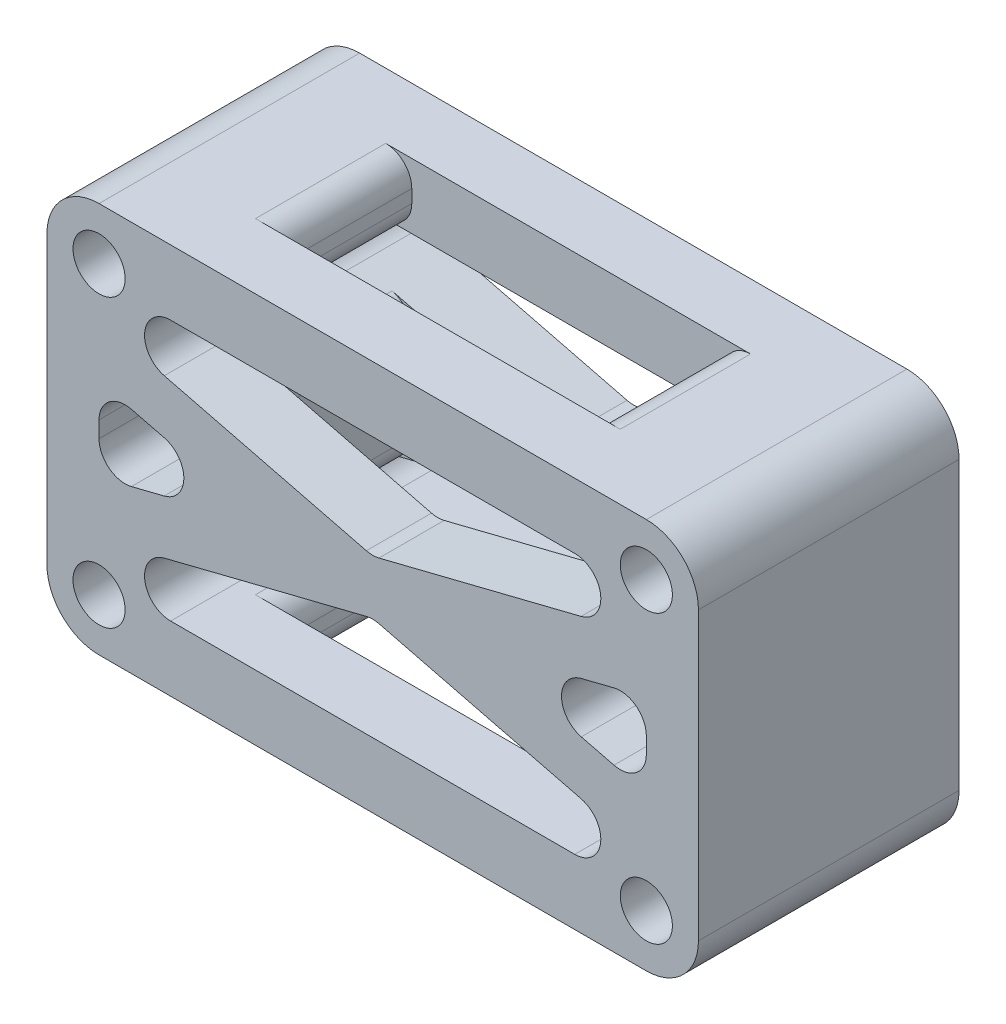
SolidWorks part; units mm, degrees
material "ABS"
ref_plane "Front" through (0, 0, 0) normal (0, 0, 1) x (1, 0, 0)
ref_plane "Top" through (0, 0, 0) normal (0, 1, 0) x (1, 0, 0)
ref_plane "Right" through (0, 0, 0) normal (1, 0, 0) x (0, 0, -1)
sketch "草图1" plane through (0, 0, 0) normal (0, 0, 1) x (1, 0, 0)
  line L1 (-12.5, -7.5) -> (12.5, -7.5)
  line L2 (-12.5, -7.5) -> (-12.5, 7.5)
  line L3 (-12.5, 7.5) -> (12.5, 7.5)
  line L4 (12.5, -7.5) -> (12.5, 7.5)
  line L5 (0, 7.5) -> (0, -7.5) construction
  line L6 (-12.5, 0) -> (12.5, 0) construction
  point P0 (0, 0)
  dimension "D1" = 15
  dimension "D2" = 25
extrude "凸台-拉伸1" add sketch "草图1" along normal blind 10
sketch "草图2" plane through (0, 0, 10) normal (0, 0, 1) x (1, 0, 0)
  line L0 (-0.2425, -1.0914) -> (-7.9963, -3.0299) construction
  line L1 (7.9963, -3.0299) -> (0.2425, -1.0914) construction
  line L2 (-0.2425, -1.0914) -> (-7.9963, -3.0299)
  line L3 (7.9963, -3.0299) -> (0.2425, -1.0914)
  line L4 (-1.5989, 0) -> (2.2438, 0) construction
  line L5 (7.7538, 5) -> (-7.7538, 5)
  line L6 (7.9963, 3.0299) -> (0.2425, 1.0914)
  line L7 (-0.2425, 1.0914) -> (-7.9963, 3.0299)
  line L8 (0, 0.633) -> (0, -0.5198) construction
  line L9 (-9.2575, -1.2836) -> (-8.0037, -0.9701)
  line L10 (-9.2575, 1.2836) -> (-8.0037, 0.9701)
  line L11 (10.5, 0.3134) -> (10.5, -0.3134)
  line L12 (7.7538, -5) -> (-7.7538, -5) construction
  line L13 (7.7538, -5) -> (-7.7538, -5)
  line L14 (12.5, -7.5) -> (12.5, 7.5) construction
  line L15 (-10.5, 0.3134) -> (-10.5, -0.3134)
  line L16 (9.2575, 1.2836) -> (8.0037, 0.9701)
  line L17 (9.2575, -1.2836) -> (8.0037, -0.9701)
  arc A0 (0.2425, -1.0914) -> (-0.2425, -1.0914) centre (0, -2.0616) ccw construction
  arc A1 (0.2425, -1.0914) -> (-0.2425, -1.0914) centre (0, -2.0616) ccw
  arc A2 (-7.9963, -3.0299) -> (-7.7538, -5) centre (-7.7538, -4) ccw construction
  arc A3 (7.7538, -5) -> (7.9963, -3.0299) centre (7.7538, -4) ccw construction
  arc A4 (-7.9963, -3.0299) -> (-7.7538, -5) centre (-7.7538, -4) ccw
  arc A5 (7.7538, -5) -> (7.9963, -3.0299) centre (7.7538, -4) ccw
  arc A6 (0.2425, 1.0914) -> (-0.2425, 1.0914) centre (0, 2.0616) cw
  arc A7 (8.0037, 0.9701) -> (8.0037, -0.9701) centre (8.2462, 0) ccw
  arc A8 (7.7538, 5) -> (7.9963, 3.0299) centre (7.7538, 4) cw
  arc A9 (-7.9963, 3.0299) -> (-7.7538, 5) centre (-7.7538, 4) cw
  arc A10 (10.5, -0.3134) -> (9.2575, -1.2836) centre (9.5, -0.3134) cw
  arc A11 (9.2575, 1.2836) -> (10.5, 0.3134) centre (9.5, 0.3134) cw
  arc A12 (-9.2575, 1.2836) -> (-10.5, 0.3134) centre (-9.5, 0.3134) ccw
  arc A13 (-10.5, -0.3134) -> (-9.2575, -1.2836) centre (-9.5, -0.3134) ccw
  arc A14 (-8.0037, 0.9701) -> (-8.0037, -0.9701) centre (-8.2462, 0) cw
  point P6 (-10.4472, 4.1056)
  point P7 (9.5528, -5.8944)
  point P8 (-9.5528, 5.8944)
  point P9 (10.4472, -4.1056)
  point P10 (-9.5528, -5.8944)
  point P11 (10.4472, 4.1056)
  point P12 (-10.4472, -4.1056)
  point P13 (9.5528, 5.8944)
  point P14 (-10.5211, -6.8779)
  point P15 (11.4789, 5.1221)
  point P16 (-11.4789, 5.1221)
  point P17 (10.5211, -6.8779)
  point P18 (-11.4789, -5.1221)
  point P19 (10.5211, 6.8779)
  point P20 (-10.5211, 6.8779)
  point P21 (11.4789, -5.1221)
  dimension "D2" = 1
  dimension "D1" = 2
fillet "圆角4" radius 2 4 edges at (-12.5, 7.5, 5) (12.5, -7.5, 5) (12.5, 7.5, 5) (-12.5, -7.5, 5)
extrude "切除-拉伸3" cut sketch "草图2" against normal blind 10
sketch "草图3" plane through (0, 0, 10) normal (0, 0, 1) x (1, 0, 0)
  line L0 (0, 3.0049) -> (0, -1.7372) construction
  line L1 (-3.0112, 0) -> (3.1966, 0) construction
  circle A0 centre (-10.5, 5.5) radius 1
  circle A1 centre (10.5, 5.5) radius 1
  circle A2 centre (10.5, -5.5) radius 1
  circle A3 centre (-10.5, -5.5) radius 1
  dimension "D1" = 2
extrude "切除-拉伸4" cut sketch "草图3" against normal blind 10
sketch "草图4" plane through (0, 7.5, 0) normal (0, 1, 0) x (1, 0, 0)
  line L1 (-6, -7.5) -> (6, -7.5)
  line L2 (-6, -7.5) -> (-6, -2.5)
  line L3 (-6, -2.5) -> (6, -2.5)
  line L4 (6, -7.5) -> (6, -2.5)
  line L5 (-6, -7.5) -> (6, -2.5) construction
  line L6 (-6, -2.5) -> (6, -7.5) construction
  point P0 (0, -5)
  point P5 (0, -5)
  point P6 (0, -5)
  dimension "D1" = 12
  dimension "D2" = 5
extrude "切除-拉伸5" cut sketch "草图4" against normal through all both and the other way through all
fillet "圆角5" radius 1 12 edges at (6, -5, 5) (-6, -7.5, 5) (6, -7.5, 5) (-6, -5, 5) (6, -2.5308, 5) (6, 2.5308, 5) (-6, -2.5308, 5) (-6, 2.5308, 5) (6, 7.5, 5) (-6, 5, 5) (6, 5, 5) (-6, 7.5, 5)
